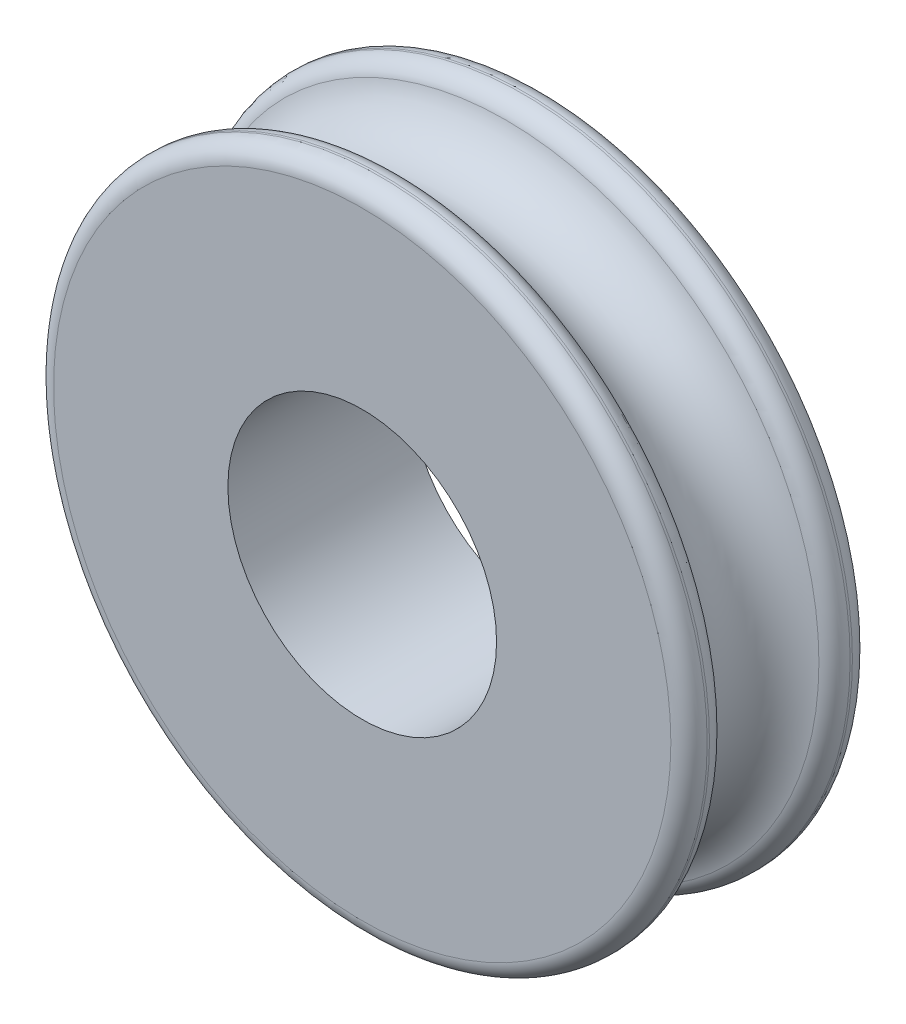
SolidWorks part; units mm, degrees
ref_plane "Front Plane" through (0, 0, 0) normal (0, 0, 1) x (1, 0, 0)
ref_plane "Top Plane" through (0, 0, 0) normal (0, 1, 0) x (1, 0, 0)
ref_plane "Right Plane" through (0, 0, 0) normal (1, 0, 0) x (0, 0, -1)
sketch "Эскиз1" plane through (0, 0, 0) normal (0, 0, 1) x (1, 0, 0)
  circle A0 centre (0, 0) radius 3.7
  circle A1 centre (0, 0) radius 9
  dimension "D1" = 7.4
  dimension "D2" = 18
extrude "Бобышка-Вытянуть1" add sketch "Эскиз1" along normal mid plane 5
sketch "Эскиз3" plane through (0, 0, 0) normal (0, 1, 0) x (1, 0, 0)
  line L0 (-13.6733, 0) -> (12.4977, 0) construction
  line L2 (9, -2.5) -> (9, 2.5) construction
  circle A0 centre (9, 0) radius 1.5
  point P5 (9, 0)
  dimension "D1" = 3
sketch "Эскиз4" plane through (0, 0, 0) normal (0, 0, 1) x (1, 0, 0)
  circle A0 centre (0, 0) radius 9 construction
  circle A1 centre (0, 0) radius 9
sweep "Вырез-По траектории1" cut profiles "Эскиз3" path "Эскиз4"
fillet "Скругление1" radius 0.5 2 edges at (9, 0, 2.5) (9, 0, -2.5)
fillet "Скругление2" radius 0.5 2 edges at (-9, 0, 1.5) (9, 0, -1.5)
